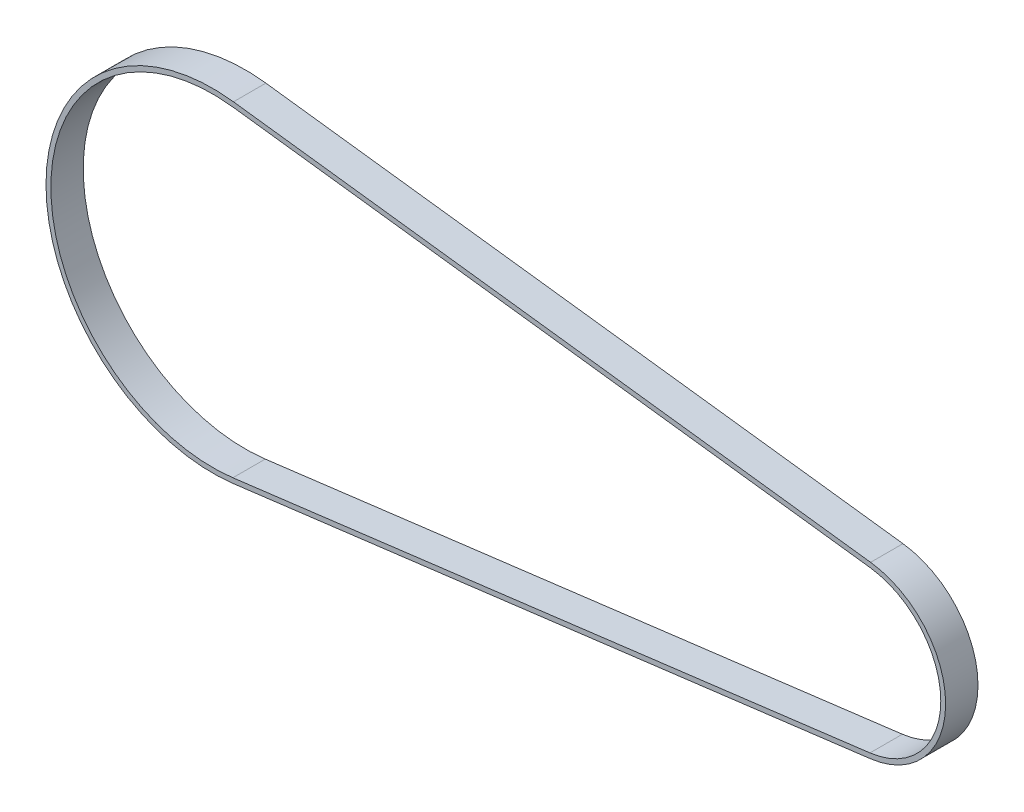
SolidWorks part; units mm, degrees
ref_plane "前视基准面" through (0, 0, 0) normal (0, 0, 1) x (1, 0, 0)
ref_plane "上视基准面" through (0, 0, 0) normal (0, 1, 0) x (1, 0, 0)
ref_plane "右视基准面" through (0, 0, 0) normal (1, 0, 0) x (0, 0, -1)
sketch "草图1" plane through (0, 0, 0) normal (0, 0, 1) x (1, 0, 0)
  line L0 (-387.5, 99.2157) -> (6.25, 49.6078)
  line L1 (-387.5, -99.2157) -> (6.25, -49.6078)
  circle A0 centre (0, 0) radius 50 construction
  circle A1 centre (-400, 0) radius 100 construction
  arc A2 (-387.5, 99.2157) -> (-387.5, -99.2157) centre (-400, 0) ccw
  arc A3 (6.25, -49.6078) -> (6.25, 49.6078) centre (0, 0) ccw
  point P8 (92.388, 100)
  point P11 (-449.3207, 107.0043)
extrude "拉伸-薄壁1" add sketch "草图1" along normal mid plane 20 thin thin type one direction wall 3
